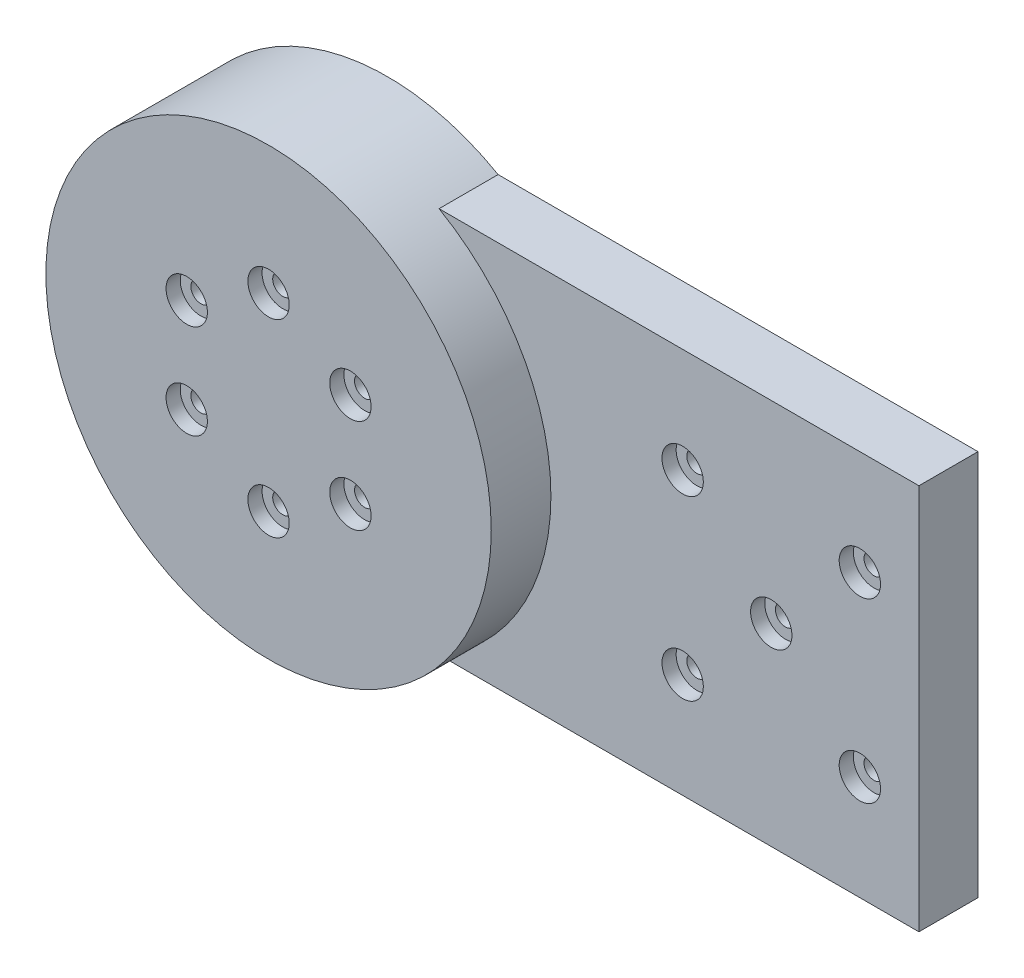
SolidWorks part; units mm, degrees
material "7075-O (SS)"
ref_plane "Front" through (0, 0, 0) normal (0, 0, 1) x (1, 0, 0)
ref_plane "Top" through (0, 0, 0) normal (0, 1, 0) x (1, 0, 0)
ref_plane "Right" through (0, 0, 0) normal (1, 0, 0) x (0, 0, -1)
sketch "Croquis1" plane through (0, 0, 0) normal (0, 0, 1) x (1, 0, 0)
  circle A0 centre (0, 0) radius 37.7
  dimension "D1" = 75.4
extrude "Saliente-Extruir1" add sketch "Croquis1" along normal blind 7
hole_wizard "Refrentado para tornillo con cabeza troncocónica de M31" positions "Croquis2" profile "Croquis3" counterbore size "M3" standard "Ansi Metric" end condition up to next
sketch "Croquis2" plane through (0, 0, 7) normal (0, 0, 1) x (1, 0, 0)
  line L0 (0, -3.85) -> (0, 3.85) construction
  line L1 (3.85, 0) -> (-3.85, 0) construction
  point P0 (0, 16)
  point P11 (13.8564, 8)
  point P12 (13.8564, -8)
  point P13 (0, -16)
  point P14 (-13.8564, -8)
  point P15 (-13.8564, 8)
  dimension "D1" = 16
  dimension "D2" = 6
sketch "Croquis3" plane through (0, 16, 7) normal (1, 0, 0) x (0, -1, 0)
  line L0 (0, 0) -> (0, 7)
  line L1 (0, 7) -> (1.7, 7)
  line L3 (1.7, 7) -> (1.7, 2.4)
  line L4 (1.7, 2.4) -> (3.5, 2.4)
  line L5 (3.5, 2.4) -> (3.5, 0)
  line L7 (3.5, 0) -> (0, 0)
  line L11 (0, -6.35) -> (0, 107.95) construction
  dimension "Diámetro de taladro hasta el siguiente" = 3.4
  dimension "Profundidad de taladro hasta el siguiente" = 7
  dimension "Diámetro de refrentado" = 7
  dimension "Profundidad de refrentado" = 2.4
sketch "Croquis4" plane through (0, 0, 0) normal (0, 0, -1) x (-1, 0, 0)
  circle A0 centre (0, 0) radius 32.8
  circle A1 centre (0, 0) radius 37.7 construction
  circle A2 centre (0, 0) radius 37.7
  dimension "D1" = 65.6
extrude "Saliente-Extruir2" add sketch "Croquis4" along normal blind 13.1
sketch "Croquis5" plane through (0, 0, -13.1) normal (0, 0, -1) x (-1, 0, 0)
  line L0 (-18.7617, 32.7) -> (-100, 32.7)
  line L1 (-100, 32.7) -> (-100, -32.7)
  line L2 (-100, -32.7) -> (-18.7617, -32.7)
  line L3 (11.6038, 0) -> (-11.6038, 0) construction
  line L4 (0, 11.6038) -> (0, -11.6038) construction
  circle A0 centre (0, 0) radius 37.7 construction
  arc A1 (-18.7617, 32.7) -> (-18.7617, -32.7) centre (0, 0) ccw
  point P3 (-100, 0)
  dimension "D1" = 65.4
  dimension "D2" = 100
extrude "Saliente-Extruir3" add sketch "Croquis5" against normal blind 10
hole_wizard "Refrentado para tornillo con cabeza troncocónica de M32" positions "Croquis6" profile "Croquis7" counterbore size "M3" standard "Ansi Metric" end condition up to next
sketch "Croquis6" plane through (0, 0, -3.1) normal (0, 0, 1) x (1, 0, 0)
  line L1 (60, -15) -> (90, -15) construction
  line L2 (60, -15) -> (60, 15) construction
  line L3 (60, 15) -> (90, 15) construction
  line L4 (90, -15) -> (90, 15) construction
  line L5 (60, -15) -> (90, 15) construction
  line L6 (60, 15) -> (90, -15) construction
  line L7 (11.055, 0) -> (-11.055, 0) construction
  line L8 (100, 32.7) -> (100, -32.7) construction
  point P1 (75, 0)
  point P2 (90, 15)
  point P27 (60, -15)
  point P28 (60, 15)
  point P29 (90, -15)
  dimension "D1" = 25
  dimension "D2" = 30
sketch "Croquis7" plane through (75, 0, -3.1) normal (1, 0, 0) x (0, -1, 0)
  line L0 (0, 0) -> (0, 10)
  line L1 (0, 10) -> (1.7, 10)
  line L3 (1.7, 10) -> (1.7, 2.4)
  line L4 (1.7, 2.4) -> (3.5, 2.4)
  line L5 (3.5, 2.4) -> (3.5, 0)
  line L7 (3.5, 0) -> (0, 0)
  line L11 (0, -6.35) -> (0, 107.95) construction
  dimension "Diámetro de taladro hasta el siguiente" = 3.4
  dimension "Profundidad de taladro hasta el siguiente" = 10
  dimension "Diámetro de refrentado" = 7
  dimension "Profundidad de refrentado" = 2.4
